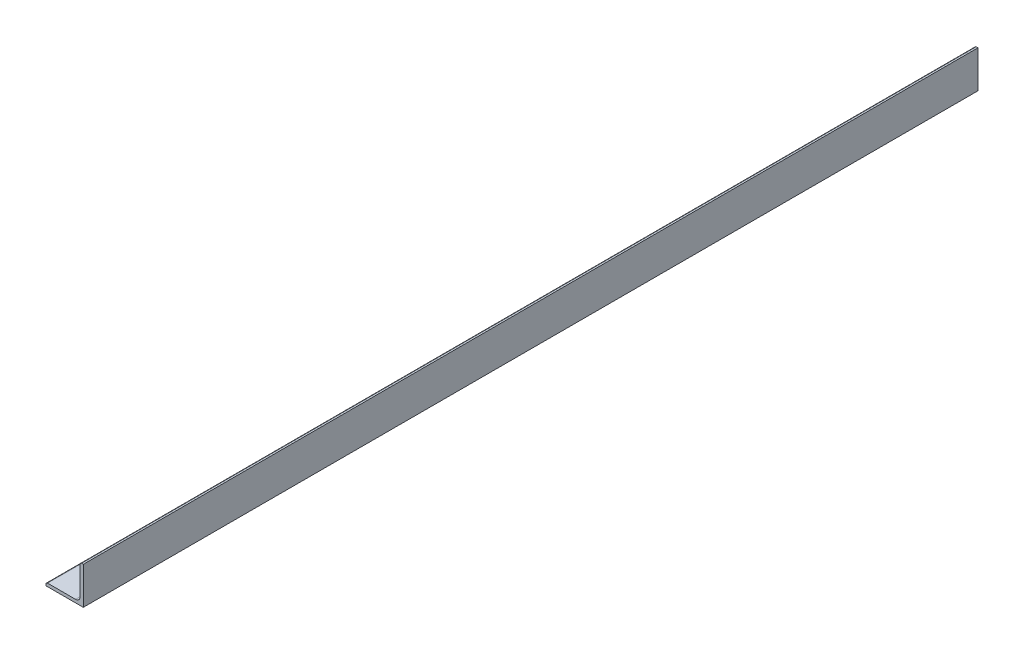
SolidWorks part; units mm, degrees
ref_plane "Front Plane" through (0, 0, 0) normal (0, 0, 1) x (1, 0, 0)
ref_plane "Top Plane" through (0, 0, 0) normal (0, 1, 0) x (1, 0, 0)
ref_plane "Right Plane" through (0, 0, 0) normal (1, 0, 0) x (0, 0, -1)
sketch "Sketch0" plane through (0, 0, 0) normal (0, 0, 1) x (1, 0, 0)
  line L0 (-19.05, -19.05) -> (19.05, -19.05)
  line L1 (19.05, -19.05) -> (19.05, 19.05)
  line L2 (19.05, 0) -> (0, 0) construction
  line L3 (0, 0) -> (0, -19.05) construction
  line L4 (15.875, -11.0998) -> (15.875, 19.05) construction
  line L5 (11.0998, -15.875) -> (-19.05, -15.875) construction
  arc A0 (15.875, -11.0998) -> (11.0998, -15.875) centre (11.0998, -11.0998) cw
  point P3 (14.4764, -14.4764)
  dimension "Inside Corner Radius" = 4.7752
  dimension "Outside Height" = 38.1
  dimension "Inside Height" = 34.925
  dimension "Inside Width" = 34.925
  dimension "Wall Thickness" = 3.175
  dimension "D1" = 3.175
  dimension "Outside Width" = 38.1
sketch "Sketch1" plane through (0, 0, 0) normal (1, 0, 0) x (0, 0, -1)
  line L0 (457.2, 0) -> (-457.2, 0)
  point P4 (0, 0)
  dimension "Length" = 914.4
sketch "Sketch2" plane through (0, 0, 0) normal (0, 0, 1) x (1, 0, 0)
  line L0 (-19.05, -19.05) -> (19.05, -19.05)
  line L1 (19.05, -19.05) -> (19.05, 19.05)
  line L2 (19.05, 19.05) -> (15.875, 19.05) construction
  line L3 (15.875, 17.4625) -> (15.875, -11.0998)
  line L4 (11.0998, -15.875) -> (-17.4625, -15.875)
  line L5 (-19.05, -19.05) -> (-19.05, -15.875) construction
  line L6 (17.4625, 19.05) -> (19.05, 19.05)
  line L7 (-19.05, -17.4625) -> (-19.05, -19.05)
  line L8 (19.05, 0) -> (0, 0) construction
  line L9 (0, 0) -> (0, -19.05) construction
  arc A0 (15.875, 17.4625) -> (17.4625, 19.05) centre (17.4625, 17.4625) cw
  arc A1 (-19.05, -17.4625) -> (-17.4625, -15.875) centre (-17.4625, -17.4625) cw
  arc A2 (15.875, -11.0998) -> (11.0998, -15.875) centre (11.0998, -11.0998) cw
  dimension "Inside Radius" = 4.7752
  dimension "Height" = 38.1
  dimension "Width" = 38.1
  dimension "Thickness" = 3.175
extrude "Boss-Extrude1" add sketch "Sketch2" along normal mid plane 914.4
sketch "Break Locations" plane through (0, 0, 0) normal (1, 0, 0) x (0, 0, -1)
  line L0 (-418.338, 0) -> (418.338, 0)
  line L1 (-457.2, -19.05) -> (-457.2, 19.05) construction
  line L2 (457.2, -19.05) -> (457.2, 19.05) construction
  point P0 (-424.815, 0)
  point P1 (424.815, 0)
  point P10 (0, 0)
  point P11 (418.338, 0)
  point P13 (-418.338, 0)
  dimension "D1" = 32.385
  dimension "D2" = 32.385
  dimension "D3" = 38.862
equation "\"D1@Break Locations\" = .85 * \"Height@Sketch2\""
equation "\"D2@Break Locations\"=\"D1@Break Locations\""
equation "\"Thickness@Sketch2\"=\"wall thickness@sketch0\""
equation "\"Height@Sketch2\"=\"outside height@sketch0\""
equation "\"Width@Sketch2\"=\"outside width@sketch0\""
equation "\"Inside Radius@Sketch2\"=\"inside corner radius@sketch0\""
equation "\"Length@Boss-Extrude1\"=\"length@sketch1\""
equation "\"D3@Break Locations\"=\"D2@Break Locations\"*1.2"
equation "\"D1@Sketch0\"=\"Wall Thickness@Sketch0\""
